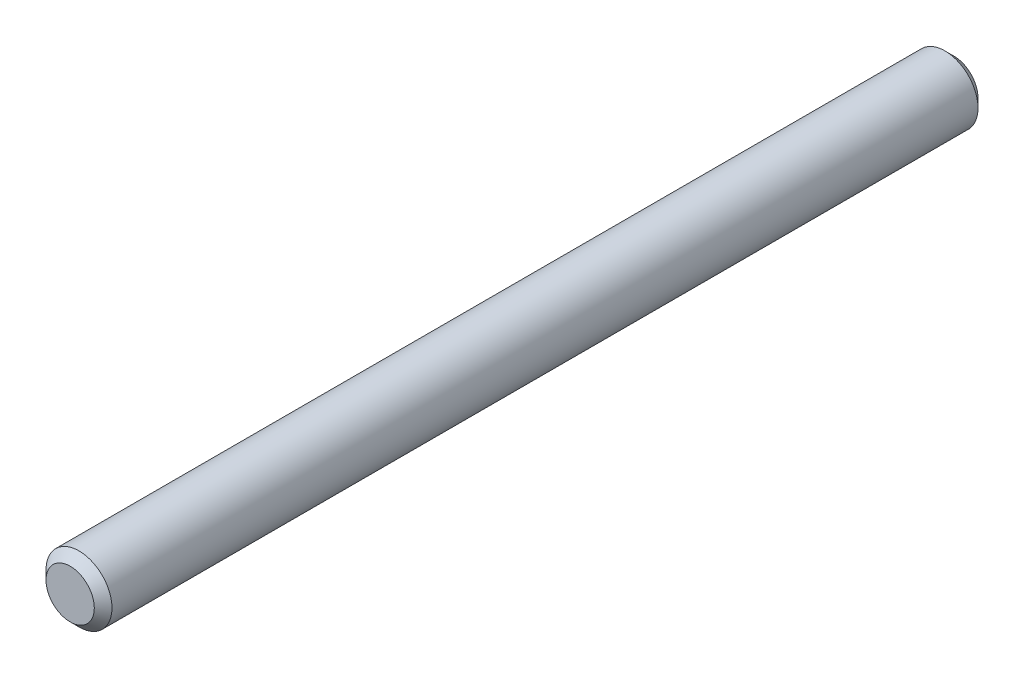
SolidWorks part; units mm, degrees
material "Alloy Steel"
ref_plane "Front Plane" through (0, 0, 0) normal (0, 0, 1) x (1, 0, 0)
ref_plane "Top Plane" through (0, 0, 0) normal (0, 1, 0) x (1, 0, 0)
ref_plane "Right Plane" through (0, 0, 0) normal (1, 0, 0) x (0, 0, -1)
sketch "Sketch1" plane through (0, 0, 0) normal (0, 0, 1) x (1, 0, 0)
  circle A0 centre (0, 0) radius 1.4224
  dimension "D1" = 2.8448
extrude "Extrude1" add sketch "Sketch1" against normal blind 38.1
cosmetic thread "Cosmetic Thread1"
chamfer "Chamfer1" distance 0.381 angle 45 2 edges at (1.4224, 0, -38.1) (1.4224, 0, 0)
